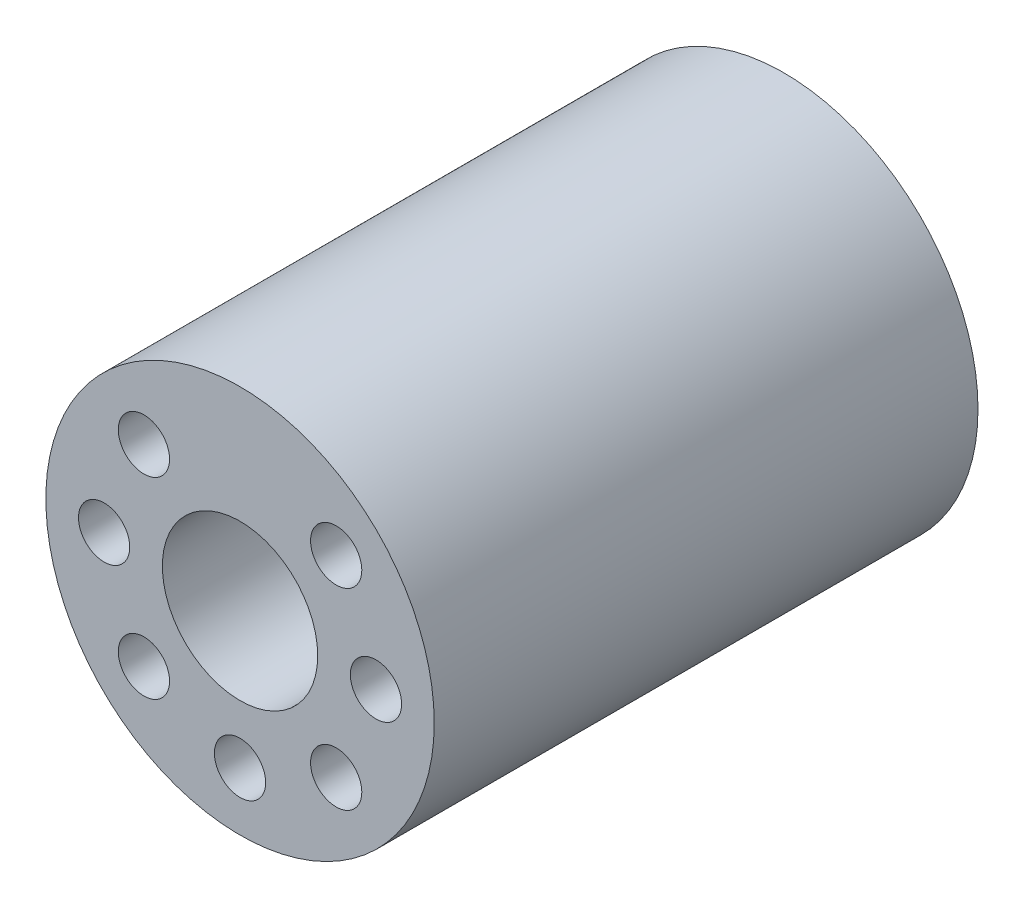
SolidWorks part; units mm, degrees
ref_plane "Front Plane" through (0, 0, 0) normal (0, 0, 1) x (1, 0, 0)
ref_plane "Top Plane" through (0, 0, 0) normal (0, 1, 0) x (1, 0, 0)
ref_plane "Right Plane" through (0, 0, 0) normal (1, 0, 0) x (0, 0, -1)
sketch "Sketch1" plane through (0, 0, 0) normal (0, 0, 1) x (1, 0, 0)
  circle A0 centre (0, 0) radius 25
  circle A1 centre (0, 0) radius 10
  dimension "D1" = 50
extrude "Boss-Extrude1" add sketch "Sketch1" along normal blind 70
sketch "Sketch3" plane through (0, 0, 70) normal (0, 0, 1) x (1, 0, 0)
  line L0 (0, 10) -> (0, 25) construction
  circle A0 centre (0, 0) radius 10 construction
  circle A1 centre (0, 0) radius 25 construction
  circle A3 centre (12.3744, 12.3744) radius 3.3
  circle A4 centre (17.5, 0) radius 3.3
  circle A5 centre (12.3744, -12.3744) radius 3.3
  circle A6 centre (0, -17.5) radius 3.3
  circle A7 centre (-12.3744, -12.3744) radius 3.3
  circle A8 centre (-17.5, 0) radius 3.3
  circle A9 centre (-12.3744, 12.3744) radius 3.3
  point P25 (0, 0)
extrude "Cut-Extrude1" cut sketch "Sketch3" against normal blind 20
sketch "Sketch4" plane through (0, 0, 0) normal (0, 0, -1) x (-1, 0, 0)
  line L0 (0, 10) -> (0, 25) construction
  circle A0 centre (0, 0) radius 10
  circle A2 centre (0, 17.5) radius 3.3
  circle A3 centre (12.3744, 12.3744) radius 3.3
  circle A4 centre (17.5, 0) radius 3.3
  circle A5 centre (12.3744, -12.3744) radius 3.3
  circle A6 centre (0, -17.5) radius 3.3
  circle A7 centre (-12.3744, -12.3744) radius 3.3
  circle A8 centre (-17.5, 0) radius 3.3
  circle A9 centre (-12.3744, 12.3744) radius 3.3
  point P25 (0, 0)
  dimension "D1" = 8
extrude "Cut-Extrude2" cut sketch "Sketch4" against normal blind 20 contours L0 A2 | A2 L0 | A3 | A4 | A5 | A6 | A7 | A8
